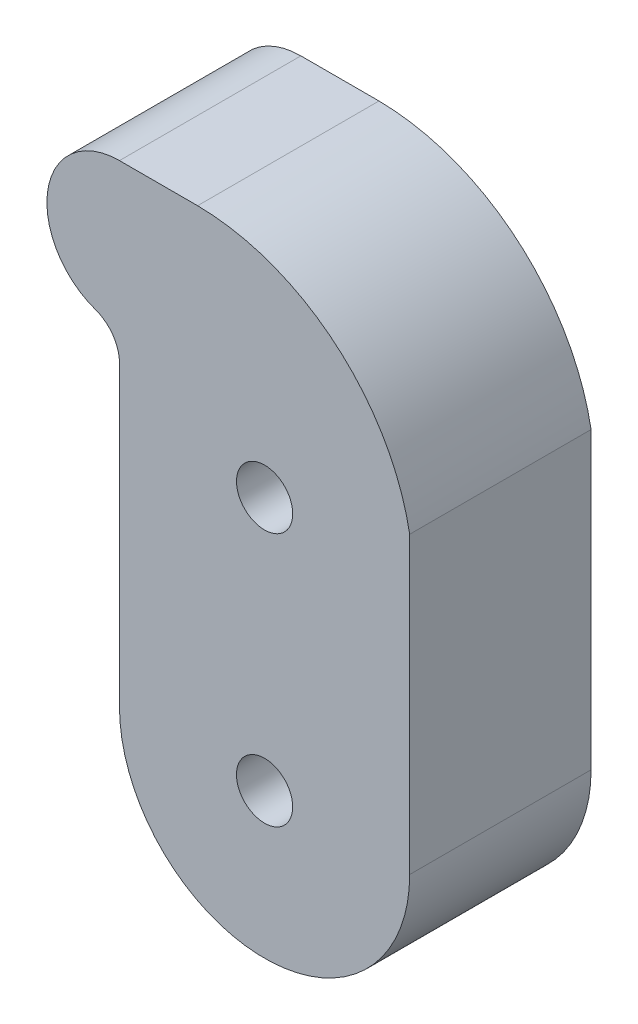
SolidWorks part; units mm, degrees
ref_plane "Płaszczyzna przednia" through (0, 0, 0) normal (0, 0, 1) x (1, 0, 0)
ref_plane "Płaszczyzna górna" through (0, 0, 0) normal (0, 1, 0) x (1, 0, 0)
ref_plane "Płaszczyzna prawa" through (0, 0, 0) normal (1, 0, 0) x (0, 0, -1)
sketch "Szkic1" plane through (0, 0, 0) normal (0, 0, 1) x (1, 0, 0)
  line L6 (-179.1268, 83.6172) -> (-183.4349, 83.6172)
  line L7 (-183.4349, 73.9603) -> (-183.4349, 57.5308)
  line L8 (-167.4349, 57.5308) -> (-167.4349, 73.7779)
  arc A0 (-183.4349, 57.5308) -> (-167.4349, 57.5308) centre (-175.4349, 57.5308) ccw
  circle A1 centre (-175.4349, 57.5308) radius 1.55
  circle A2 centre (-175.4349, 71.5308) radius 1.55
  arc A6 (-183.4349, 83.6172) -> (-184.7682, 75.8459) centre (-183.4349, 79.6172) ccw
  arc A8 (-167.4349, 73.7779) -> (-179.1268, 83.6172) centre (-179.2388, 71.6177) ccw
  arc A23 (-183.4349, 73.9603) -> (-184.7682, 75.8459) centre (-185.4349, 73.9603) ccw
  dimension "D2" = 3.1
  dimension "D3" = 3.1
  dimension "D4" = 14
  dimension "D5" = 6.45
extrude "Dodanie-wyciągnięcie1" add sketch "Szkic1" along normal blind 10
